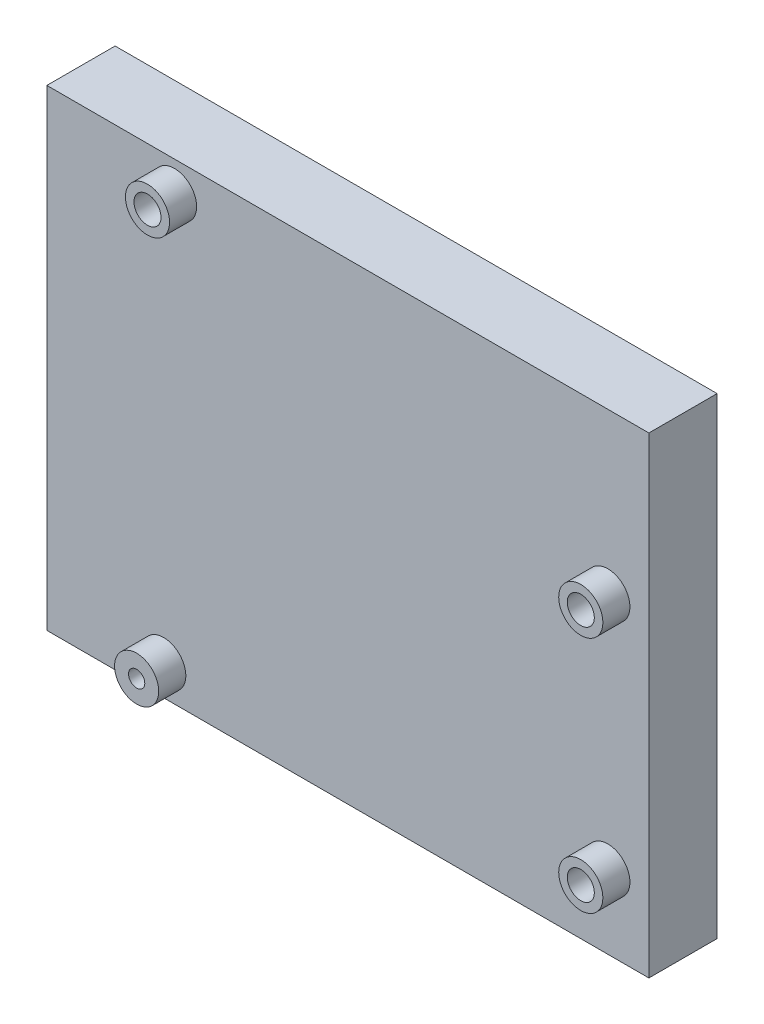
SolidWorks part; units mm, degrees
ref_plane "Front Plane" through (0, 0, 0) normal (0, 0, 1) x (1, 0, 0)
ref_plane "Top Plane" through (0, 0, 0) normal (0, 1, 0) x (1, 0, 0)
ref_plane "Right Plane" through (0, 0, 0) normal (1, 0, 0) x (0, 0, -1)
sketch "Sketch1" plane through (0, 0, 0) normal (0, 0, 1) x (1, 0, 0)
  line L0 (0, 26.67) -> (0, -26.67) construction
  line L6 (-35.29, -27.67) -> (35.29, -27.67)
  line L7 (-34.29, 0) -> (34.29, 0) construction
  line L8 (31.75, 26.67) -> (-34.29, 26.67) construction
  line L9 (-34.29, 26.67) -> (-34.29, -26.67) construction
  line L10 (-34.29, -26.67) -> (31.75, -26.67) construction
  line L11 (31.75, -26.67) -> (31.75, -13.716) construction
  line L12 (31.75, -13.716) -> (34.29, -11.176) construction
  line L13 (34.29, -11.176) -> (34.29, 21.59) construction
  line L14 (34.29, 21.59) -> (31.75, 24.13) construction
  line L15 (31.75, 24.13) -> (31.75, 26.67) construction
  line L16 (-35.29, -27.67) -> (-35.29, 27.67)
  line L17 (-35.29, 27.67) -> (35.29, 27.67)
  line L18 (35.29, -27.67) -> (35.29, 27.67)
  line L19 (-35.29, -27.67) -> (35.29, 27.67) construction
  line L20 (-35.29, 27.67) -> (35.29, -27.67) construction
  circle A6 centre (-20.32, 24.13) radius 1.5875
  circle A8 centre (30.48, 8.89) radius 1.5875
  circle A9 centre (30.48, -19.05) radius 1.5875
  circle A10 centre (-21.59, -24.13) radius 1.5875
  point P0 (0, 0)
  point P6 (0, 0)
  dimension "D1" = 1
  dimension "D2" = 1
extrude "Boss-Extrude1" add sketch "Sketch1" along normal mid plane 8
sketch "Sketch2" plane through (0, -27.67, 0) normal (0, 1, 0) x (1, 0, 0)
  line L0 (0, 0) -> (50000, 0) construction
  line L1 (0, 0) -> (0, 50000) construction
  circle A0 centre (30, 0) radius 2.5
  circle A1 centre (-30, 0) radius 2.5
  dimension "D1" = 5
  dimension "D2" = 30
extrude "Cut-Extrude1" cut sketch "Sketch2" along normal blind 6
sketch "Sketch3" plane through (0, 0, 4) normal (0, 0, 1) x (1, 0, 0)
  circle A0 centre (-20.32, 24.13) radius 2.5875
  circle A6 centre (-20.32, 24.13) radius 1.5875 construction
  circle A10 centre (-20.32, 24.13) radius 1.5875
  circle A12 centre (30.48, 8.89) radius 1.5875
  circle A13 centre (30.48, -19.05) radius 1.5875
  circle A14 centre (-21.59, -24.13) radius 2.5875
  circle A15 centre (30.48, 8.89) radius 2.5875
  circle A16 centre (30.48, -19.05) radius 2.5875
  circle A17 centre (-21.59, -24.13) radius 0.9525
  dimension "D1" = 1
extrude "Boss-Extrude2" add sketch "Sketch3" along normal blind 3.175
